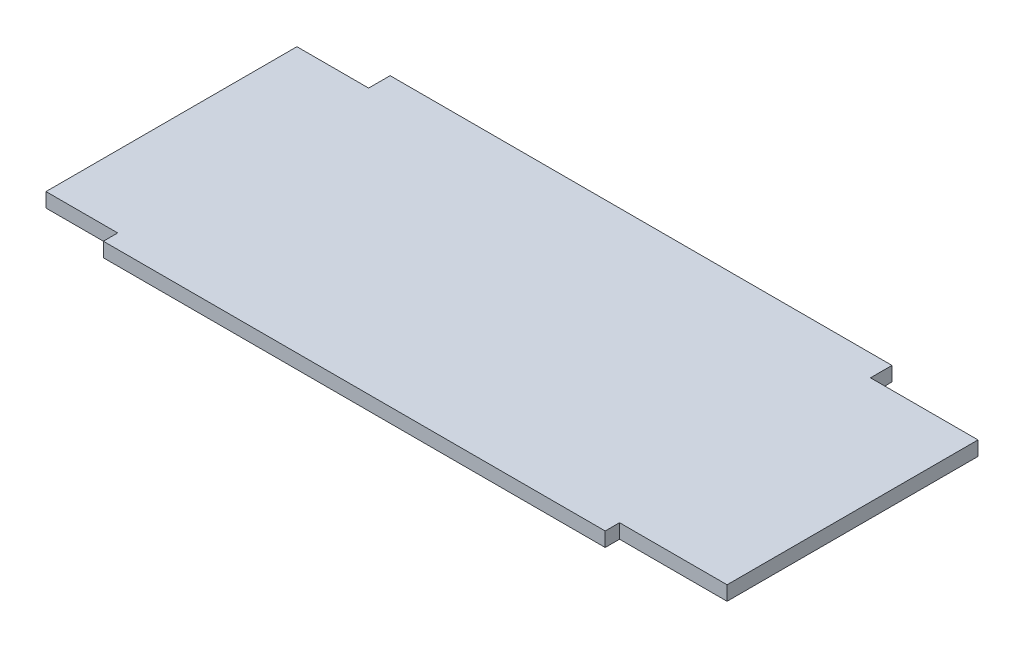
SolidWorks part; units mm, degrees
material "PVC rigido"
ref_plane "Piano frontale" through (0, 0, 0) normal (0, 0, 1) x (1, 0, 0)
ref_plane "Piano superiore" through (0, 0, 0) normal (0, 1, 0) x (1, 0, 0)
ref_plane "Piano destro" through (0, 0, 0) normal (1, 0, 0) x (0, 0, -1)
sketch "Schizzo1" plane through (0, 0, 0) normal (0, 0, 1) x (1, 0, 0)
  line L0 (78, -74.5) -> (148, -74.5) construction
  line L1 (78, -72.5) -> (148, -72.5)
  line L2 (78, -72.5) -> (78, -74.5)
  line L3 (78, -74.5) -> (148, -74.5)
  line L4 (148, -72.5) -> (148, -74.5)
extrude "Estrusione-Estrusione1" add sketch "Schizzo1" along normal up to surface (37 mm away) and the other way up to surface (3 mm away)
sketch "Schizzo2" plane through (148, 0, 0) normal (1, 0, 0) x (0, 0, -1)
  line L0 (-37, -74.5) -> (3, -74.5) construction
  line L1 (0, -72.5) -> (-35, -72.5)
  line L2 (0, -72.5) -> (0, -74.5)
  line L3 (0, -74.5) -> (-35, -74.5)
  line L4 (-35, -72.5) -> (-35, -74.5)
  line L5 (-35, -74.5) -> (-35, -72.5) construction
extrude "Estrusione-Estrusione2" add sketch "Schizzo2" along normal blind 15
sketch "Schizzo3" plane through (78, 0, 0) normal (-1, 0, 0) x (0, 0, 1)
  line L0 (37, -74.5) -> (-3, -74.5) construction
  line L1 (0, -72.5) -> (35, -72.5)
  line L2 (0, -72.5) -> (0, -74.5)
  line L3 (0, -74.5) -> (35, -74.5)
  line L4 (35, -72.5) -> (35, -74.5)
  line L5 (35, -72.5) -> (35, -74.5) construction
extrude "Estrusione-Estrusione3" add sketch "Schizzo3" along normal blind 10
